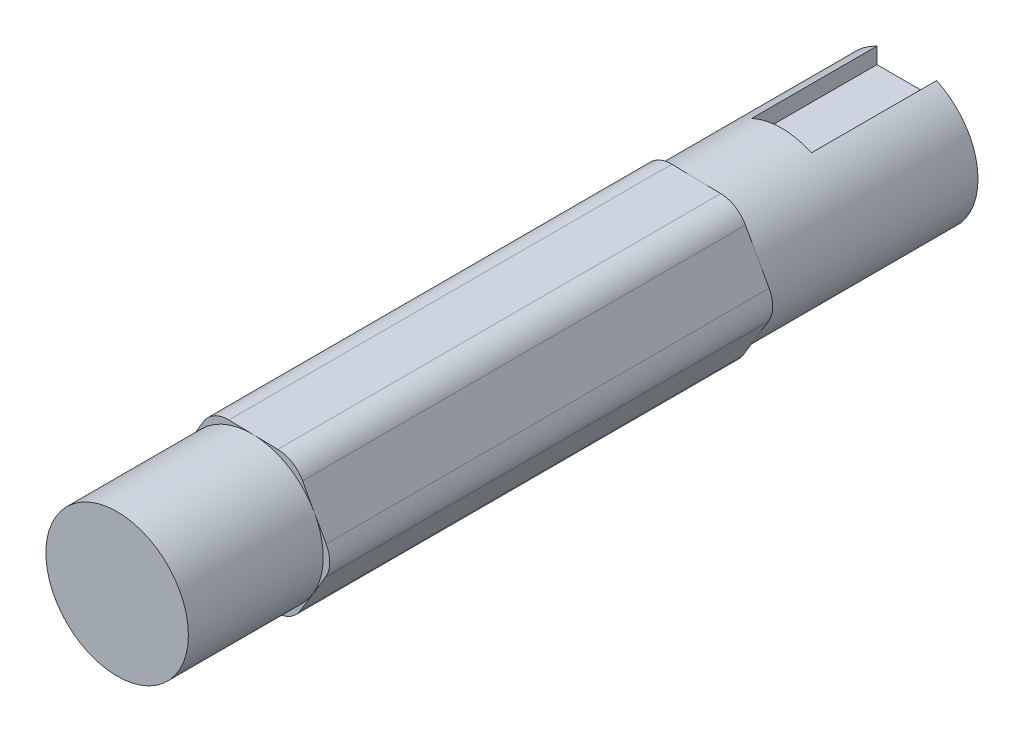
SolidWorks part; units mm, degrees
ref_plane "Front Plane" through (0, 0, 0) normal (0, 0, 1) x (1, 0, 0)
ref_plane "Top Plane" through (0, 0, 0) normal (0, 1, 0) x (1, 0, 0)
ref_plane "Right Plane" through (0, 0, 0) normal (1, 0, 0) x (0, 0, -1)
sketch "Sketch1" plane through (0, 0, 0) normal (0, 0, 1) x (1, 0, 0)
  circle A0 centre (0, 0) radius 7.4
  dimension "D1" = 14.8
extrude "Boss-Extrude1" add sketch "Sketch1" along normal blind 37 and the other way blind 45
sketch "Sketch3" plane through (0, 0, 0) normal (0, 1, 0) x (1, 0, 0)
  line L0 (-27.349, 0) -> (27.9883, 0) construction
  line L1 (-27.349, 31) -> (27.9883, 31) construction
  line L2 (-27.349, 32) -> (27.9883, 32) construction
  line L3 (-27.349, 42) -> (27.9883, 42) construction
  line L4 (27.9883, 45) -> (-27.349, 45) construction
  line L5 (-27.349, -31) -> (27.9883, -31) construction
  line L6 (-27.349, -37) -> (27.9883, -37) construction
  dimension "D1" = 31
  dimension "D2" = 1
  dimension "D3" = 10
  dimension "D4" = 3
  dimension "D5" = 31
  dimension "D6" = 6
sketch "Sketch4" plane through (0, 0, -45) normal (0, 0, -1) x (-1, 0, 0)
  line L0 (-18.2857, 7.4) -> (18.9059, 7.4) construction
  line L1 (-3.1, 9.75) -> (3.1, 9.75)
  line L2 (-3.1, 9.75) -> (-3.1, 5.05)
  line L3 (-3.1, 5.05) -> (3.1, 5.05)
  line L4 (3.1, 9.75) -> (3.1, 5.05)
  line L5 (0, 15.7597) -> (0, -12.3933) construction
  circle A0 centre (0, 0) radius 7.4 construction
  dimension "D1" = 6.2
  dimension "D2" = 4.7
extrude "Cut-Extrude1" cut sketch "Sketch4" against normal blind 13
ref_plane "Plane1" through (0, 0, 23) normal (0, 0, 1) x (1, 0, 0)
ref_plane "Plane2" through (0, 0, -23) normal (0, 0, 1) x (1, 0, 0)
sketch "Sketch5" plane through (0, 0, -23) normal (0, 0, 1) x (1, 0, 0)
  line L1 (4.4198, 7.3129) -> (-4.1233, 7.4841)
  line L2 (-4.1233, 7.4841) -> (-8.5431, 0.1711)
  line L3 (-8.5431, 0.1711) -> (-4.4198, -7.3129)
  line L4 (-4.4198, -7.3129) -> (4.1233, -7.4841)
  line L5 (4.1233, -7.4841) -> (8.5431, -0.1711)
  line L6 (8.5431, -0.1711) -> (4.4198, 7.3129)
  circle A0 centre (0, 0) radius 7.4 construction
  dimension "D1" = 14.8
extrude "Boss-Extrude2" add sketch "Sketch5" along normal up to surface (46 mm away) up to plane "Plane1"
fillet "Fillet1" radius 3 6 edges at (-4.1233, 7.4841, 0) (-8.5431, 0.1711, 0) (-4.4198, -7.3129, 0) (4.1233, -7.4841, 0) (8.5431, -0.1711, 0) (4.4198, 7.3129, 0)
